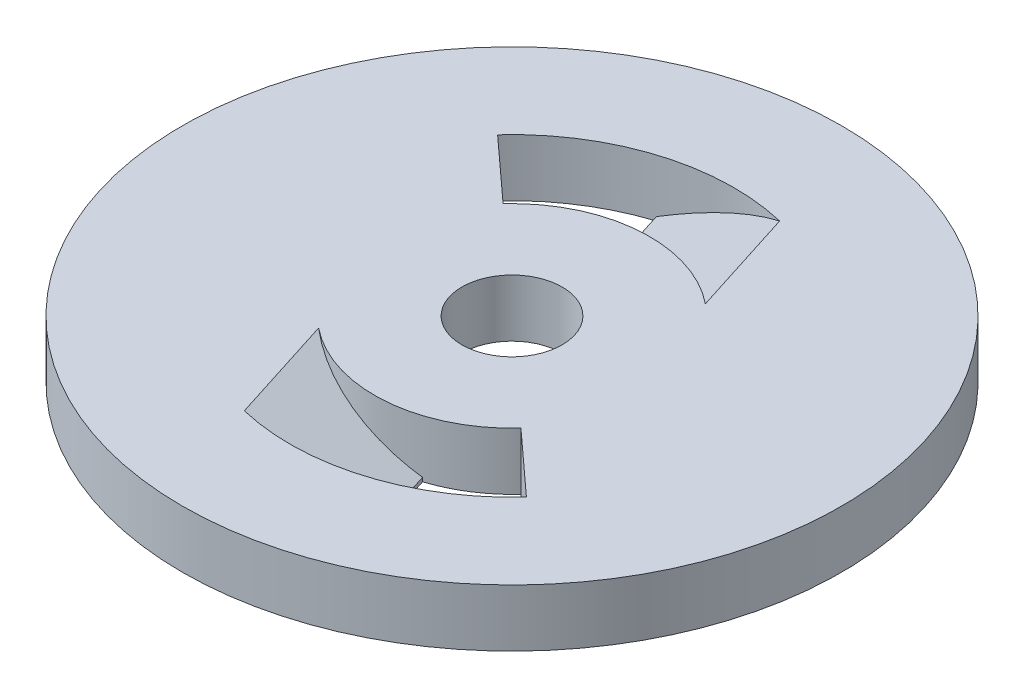
SolidWorks part; units mm, degrees
ref_plane "Front Plane" through (0, 0, 0) normal (0, 0, 1) x (1, 0, 0)
ref_plane "Top Plane" through (0, 0, 0) normal (0, 1, 0) x (1, 0, 0)
ref_plane "Right Plane" through (0, 0, 0) normal (1, 0, 0) x (0, 0, -1)
sketch "Sketch1" plane through (0, 0, 0) normal (0, 1, 0) x (1, 0, 0)
  circle A0 centre (0, 0) radius 11.5
  circle A1 centre (0, 0) radius 1.75
extrude "Boss-Extrude1" add sketch "Sketch1" along normal blind 2
sketch "Sketch2" plane through (0, 2, 0) normal (0, 1, 0) x (1, 0, 0)
  line L0 (0, 0) -> (-4.1787, 6.527) construction
  line L1 (0, 0) -> (4.2753, 2.7371) construction
  line L2 (0, 0) -> (-2.347, 7.3861) construction
  line L3 (-2.347, 7.3861) -> (0, 0) construction
  line L4 (0, 0) -> (-5.7256, 5.223) construction
  line L5 (-1.4536, 4.5746) -> (-2.347, 7.3861)
  line L6 (-3.5462, 3.2349) -> (-5.7256, 5.223)
  line L7 (5.7256, -5.223) -> (3.5462, -3.2349)
  line L8 (2.347, -7.3861) -> (1.4536, -4.5746)
  arc A0 (-5.7256, 5.223) -> (-2.347, 7.3861) centre (0, 0) cw
  arc A1 (2.347, -7.3861) -> (5.7256, -5.223) centre (0, 0) ccw
  arc A2 (-3.5462, 3.2349) -> (-1.4536, 4.5746) centre (0, 0) cw
  arc A3 (1.4536, -4.5746) -> (3.5462, -3.2349) centre (0, 0) ccw
  dimension "D1" = 7.75
  dimension "D2" = 4.8
extrude "Cut-Extrude1" cut sketch "Sketch2" against normal blind 2
chamfer "Chamfer1" distance 4 angle 25 1 edges at (-1.9003, 2, -5.9803)
chamfer "Chamfer2" distance 4 angle 25 1 edges at (1.9003, 2, 5.9803)
